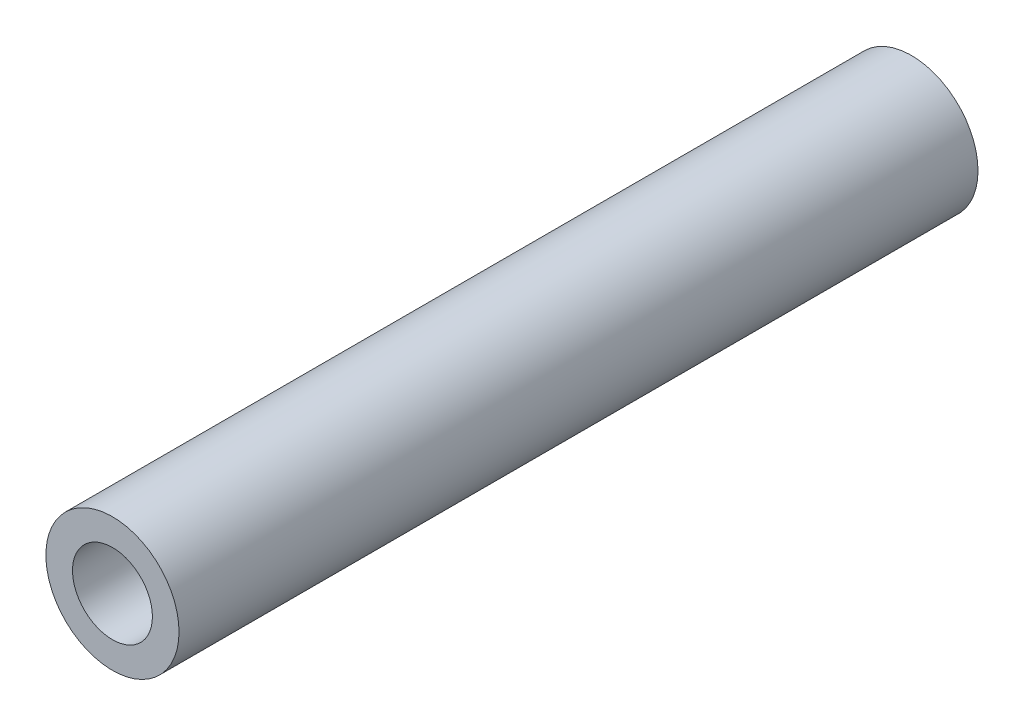
SolidWorks part; units mm, degrees
ref_plane "前视基准面" through (0, 0, 0) normal (0, 0, 1) x (1, 0, 0)
ref_plane "上视基准面" through (0, 0, 0) normal (0, 1, 0) x (1, 0, 0)
ref_plane "右视基准面" through (0, 0, 0) normal (1, 0, 0) x (0, 0, -1)
sketch "草图1" plane through (0, 0, 0) normal (0, 0, 1) x (1, 0, 0)
  circle A0 centre (0, 0) radius 2.5
  circle A1 centre (0, 0) radius 1.5
  dimension "D1" = 3
  dimension "D2" = 5
extrude "凸台-拉伸1" add sketch "草图1" along normal mid plane 30
